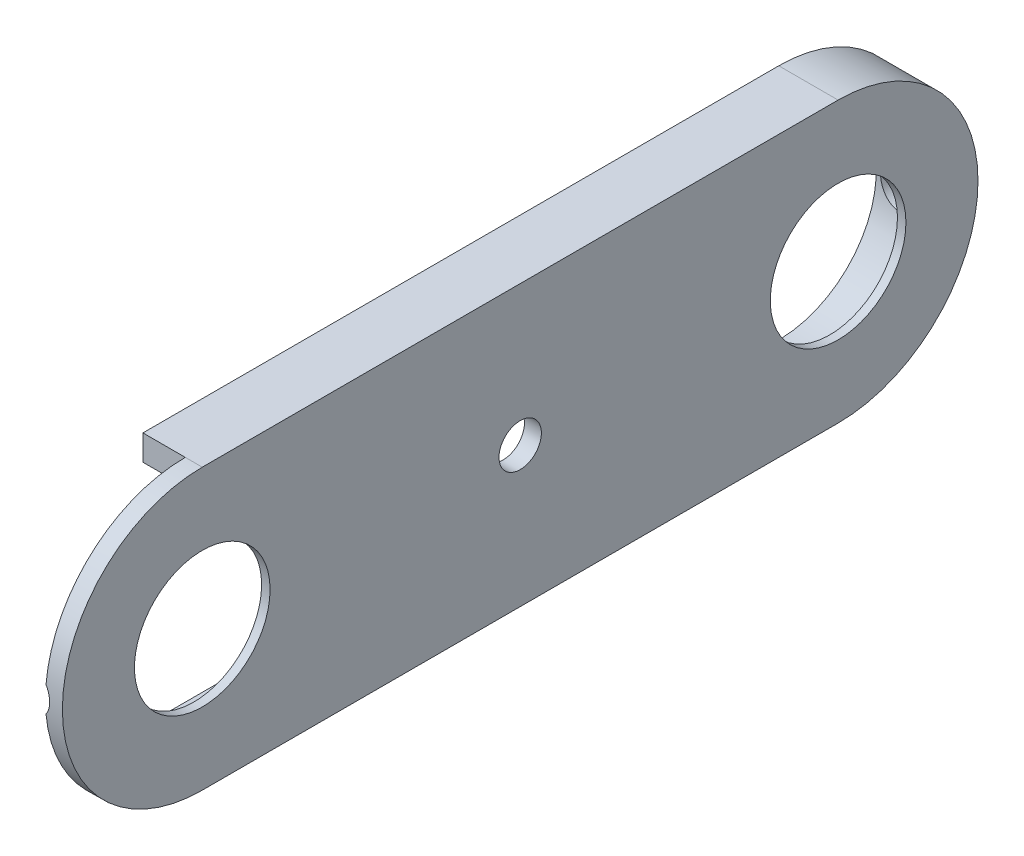
SolidWorks part; units mm, degrees
ref_plane "Front Plane" through (0, 0, 0) normal (0, 0, 1) x (1, 0, 0)
ref_plane "Top Plane" through (0, 0, 0) normal (0, 1, 0) x (1, 0, 0)
ref_plane "Right Plane" through (0, 0, 0) normal (1, 0, 0) x (0, 0, -1)
sketch "Sketch3" plane through (0, 20, 0) normal (-1, 0, 0) x (0, 1, 0)
  line L0 (-20, 37.5) -> (-20, -37.5) construction
  line L3 (-3.5, 37.5) -> (-3.5, -37.5)
  line L4 (-36.5, 37.5) -> (-36.5, -37.5)
  arc A8 (-3.5, 37.5) -> (-36.5, 37.5) centre (-20, 37.5) ccw
  arc A9 (-36.5, -37.5) -> (-3.5, -37.5) centre (-20, -37.5) ccw
  circle A10 centre (-20, -37.5) radius 11.5
  circle A11 centre (-20, 37.5) radius 11.5
  point P6 (-20, 0)
  dimension "D2" = 5
  dimension "D3" = 75
  dimension "D1" = 23
extrude "Boss-Extrude2" add sketch "Sketch3" along normal blind 1
sketch "Sketch4" plane through (0, 0, 0) normal (1, 0, 0) x (0, 0, -1)
  line L2 (37.5, 16.5) -> (-37.5, 16.5)
  line L3 (-37.5, -16.5) -> (37.5, -16.5)
  line L4 (37.5, 16.5) -> (-37.5, 16.5)
  line L5 (-37.5, -16.5) -> (37.5, -16.5)
  circle A0 centre (-37.5, 0) radius 8
  arc A2 (37.5, -16.5) -> (37.5, 16.5) centre (37.5, 0) ccw
  arc A3 (-37.5, 16.5) -> (-37.5, -16.5) centre (-37.5, 0) ccw
  arc A4 (37.5, -16.5) -> (37.5, 16.5) centre (37.5, 0) ccw
  arc A5 (-37.5, 16.5) -> (-37.5, -16.5) centre (-37.5, 0) ccw
  circle A7 centre (37.5, 0) radius 8
  dimension "D2" = 16
  dimension "D1" = 0
extrude "Boss-Extrude3" add sketch "Sketch4" along normal blind 1
sketch "Sketch5" plane through (-1, 0, 0) normal (-1, 0, 0) x (0, 0, 1)
  line L2 (-37.5, -16.5) -> (37.5, -16.5)
  line L3 (37.5, 16.5) -> (-37.5, 16.5)
  circle A1 centre (-37.5, 0) radius 11.5 construction
  circle A2 centre (-37.5, 0) radius 11.5
  arc A8 (-37.5, 16.5) -> (-37.5, -16.5) centre (-37.5, 0) ccw
  arc A9 (37.5, -16.5) -> (37.5, 16.5) centre (37.5, 0) ccw
  arc A10 (-37.5, 16.5) -> (-37.5, -16.5) centre (-37.5, 0) ccw
  arc A12 (-37.5, 16.5) -> (-37.5, -16.5) centre (-37.5, 0) cw
  dimension "D1" = 0
extrude "Boss-Extrude4" add sketch "Sketch5" along normal blind 5
ref_plane "Plane1" through (0, 0, 54) normal (0, 0, 1) x (1, 0, 0)
sketch "Sketch6" plane through (0, 0, 54) normal (0, 0, 1) x (1, 0, 0)
  line L0 (0, 11.5) -> (0, -11.5) construction
  line L1 (0, 11.5) -> (0, -11.5) construction
  line L2 (-6, 16.5) -> (-6, -16.5) construction
  line L3 (-6, 16.5) -> (-6, -16.5) construction
  line L4 (-6, 0) -> (0, 0) construction
  circle A0 centre (-3, 0) radius 2.5
  dimension "D1" = 2.5
extrude "Cut-Extrude1" cut sketch "Sketch6" against normal blind 10
mirror "Mirror1" about plane through (0, 0, 0) normal (0, 0, 1) of "Cut-Extrude1"
sketch "Sketch7" plane through (1, 0, 0) normal (1, 0, 0) x (0, 0, -1)
  circle A0 centre (0, 0) radius 2.5
  dimension "D1" = 2.5
extrude "Cut-Extrude2" cut sketch "Sketch7" against normal through all
sketch "Sketch11" plane through (0, -16.5, 0) normal (0, -1, 0) x (1, 0, 0)
  line L0 (-1, -37.5) -> (1, -37.5) construction
  line L1 (-1, 37.5) -> (-6, 37.5)
  line L2 (-1, 37.5) -> (-1, -37.5)
  line L3 (-1, -37.5) -> (-6, -37.5)
  line L4 (-6, 37.5) -> (-6, -37.5)
  line L5 (-6, -21) -> (-6, -54) construction
  point P7 (0, 0)
extrude "Boss-Extrude7" add sketch "Sketch11" against normal blind 3
mirror "Mirror2" about plane through (0, 0, 0) normal (0, 1, 0) of "Boss-Extrude7"
